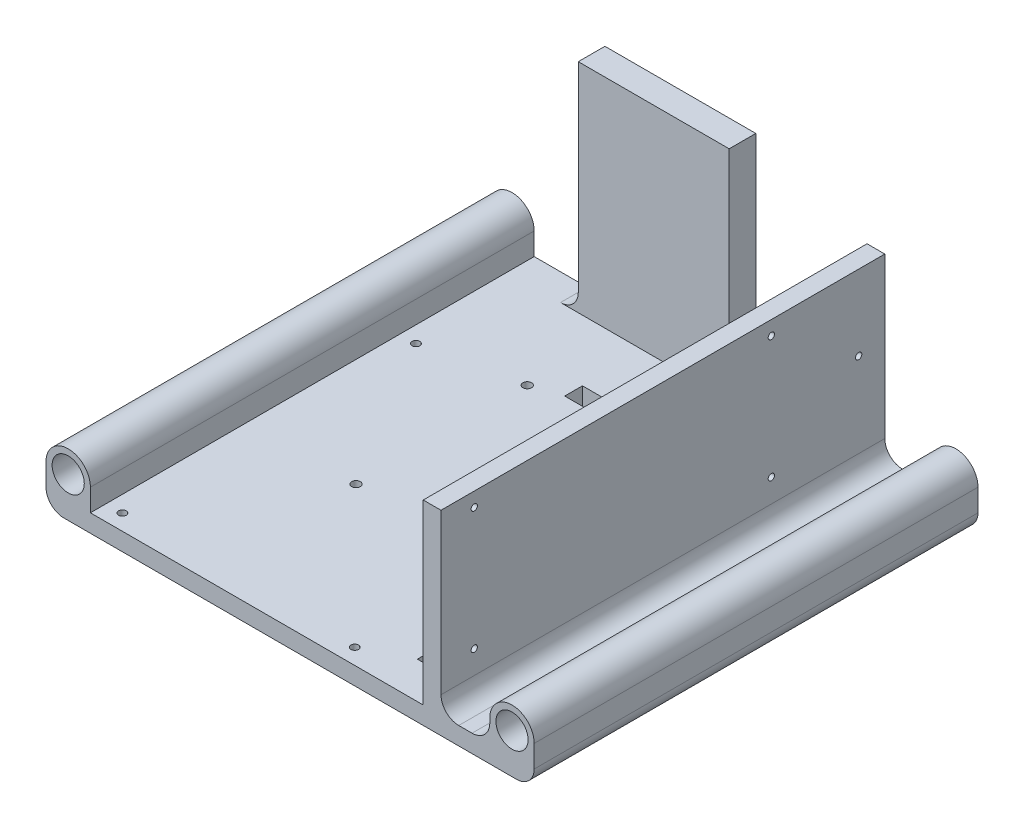
SolidWorks part; units mm, degrees
ref_plane "Front Plane" through (0, 0, 0) normal (0, 0, 1) x (1, 0, 0)
ref_plane "Top Plane" through (0, 0, 0) normal (0, 1, 0) x (1, 0, 0)
ref_plane "Right Plane" through (0, 0, 0) normal (1, 0, 0) x (0, 0, -1)
sketch "Sketch1" plane through (0, 0, 0) normal (0, 0, 1) x (1, 0, 0)
  line L21 (-0.4677, 0.9705) -> (-0.4677, -10.4595)
  line L22 (-0.4677, -10.4595) -> (139.2323, -10.4595)
  line L23 (139.2323, -10.4595) -> (139.2323, 0.9705)
  line L24 (12.2323, 0.9705) -> (12.2323, -5.3795)
  line L25 (12.2323, -5.3795) -> (126.5323, -5.3795)
  line L26 (126.5323, -5.3795) -> (126.5323, 0.9705)
  circle A8 centre (5.8823, 0.9705) radius 4.6037
  circle A9 centre (132.8823, 0.9705) radius 4.6037
  arc A13 (12.2323, 0.9705) -> (-0.4677, 0.9705) centre (5.8823, 0.9705) ccw
  arc A14 (139.2323, 0.9705) -> (126.5323, 0.9705) centre (132.8823, 0.9705) ccw
  point P23 (0, 0)
  dimension "D1" = 139.7
  dimension "D2" = 5.08
  dimension "D6" = 9.2075
  dimension "D5" = 127
extrude "Boss-Extrude1" add sketch "Sketch1" along normal blind 127
sketch "Sketch3" plane through (0, -10.4595, 0) normal (0, -1, 0) x (1, 0, 0)
  line L0 (75.7323, 119.583) -> (75.7323, 6.3354) construction
  line L2 (139.2323, 127) -> (139.2323, 0) construction
  line L20 (75.7323, 63.04) -> (81.2978, 63.04) construction
  circle A0 centre (101.1323, 81.883) radius 1.25
  circle A1 centre (43.1323, 81.883) radius 1.25
  circle A2 centre (43.1323, 32.883) radius 1.25
  circle A3 centre (101.1323, 32.883) radius 1.25
  circle A4 centre (93.2323, 9.583) radius 0.9 construction
  circle A5 centre (93.2323, 94.583) radius 0.9 construction
  circle A6 centre (75.7323, 119.583) radius 0.9 construction
  circle A7 centre (58.2323, 94.583) radius 0.9 construction
  circle A8 centre (58.2323, 9.583) radius 0.9 construction
  point P25 (130.2569, 58.4424)
  point P30 (13.2512, 58.4424)
  dimension "D5" = 2.5
  dimension "D6" = 1.8
  dimension "D1" = 58
  dimension "D2" = 49
  dimension "D3" = 38.1
  dimension "D4" = 25.4
  dimension "D7" = 35
  dimension "D8" = 17.5
  dimension "D9" = 25
  dimension "D10" = 85
  dimension "D11" = 12.7
extrude "Cut-Extrude3" cut sketch "Sketch3" against normal through all
sketch "Sketch4" plane through (0, -5.3795, 0) normal (0, 1, 0) x (1, 0, 0)
  line L0 (16.878, -38.479) -> (83.378, -38.479) construction
  line L1 (50.128, -38.479) -> (50.128, -76.4797) construction
  circle A0 centre (16.878, -38.479) radius 1.1
  circle A1 centre (16.878, -122.479) radius 1.1
  circle A2 centre (83.378, -38.479) radius 1.1
  circle A3 centre (83.378, -122.479) radius 1.1
  dimension "D1" = 2.2
  dimension "D2" = 66.5
  dimension "D3" = 84
extrude "Cut-Extrude4" cut sketch "Sketch4" against normal through all
sketch "Sketch5" plane through (0, -5.3795, 0) normal (0, 1, 0) x (1, 0, 0)
  line L0 (126.5323, 0) -> (12.2323, 0) construction
  line L1 (107.4823, 0) -> (112.5623, 0)
  line L2 (107.4823, 0) -> (107.4823, -127)
  line L3 (107.4823, -127) -> (112.5623, -127)
  line L4 (112.5623, 0) -> (112.5623, -127)
  line L5 (126.5323, -127) -> (12.2323, -127) construction
  line L6 (126.5323, -127) -> (126.5323, 0) construction
  dimension "D1" = 5.08
  dimension "D2" = 13.97
extrude "Boss-Extrude2" add sketch "Sketch5" along normal blind 50.8
sketch "Sketch6" plane through (107.4823, 0, 0) normal (-1, 0, 0) x (0, 0, 1)
  line L0 (32.475, 6.3565) -> (32.475, 41.3565) construction
  line L1 (0, 45.4205) -> (127, 45.4205) construction
  line L2 (127, 45.4205) -> (127, -5.3795) construction
  circle A0 centre (32.475, 6.3565) radius 0.9
  circle A1 centre (32.475, 41.3565) radius 0.9
  circle A2 centre (117.475, 6.3565) radius 0.9
  circle A3 centre (117.475, 41.3565) radius 0.9
  circle A4 centre (7.475, 23.8565) radius 0.9
  point P10 (32.475, 23.8565)
  dimension "D4" = 1.8
  dimension "D1" = 17.5
  dimension "D2" = 85
  dimension "D3" = 25
  dimension "D5" = 4.064
  dimension "D6" = 9.525
extrude "Cut-Extrude5" cut sketch "Sketch6" against normal up to surface (5.08 mm away) up to face at (112.5623, 20.0205, 63.5)
sketch "Sketch7" plane through (0, -5.3795, 0) normal (0, 1, 0) x (1, 0, 0)
  line L0 (107.4823, 0) -> (107.4823, -127) construction
  line L1 (101.0497, -5.08) -> (107.4823, -5.08)
  line L2 (101.0497, -5.08) -> (101.0497, -29.3604)
  line L3 (101.0497, -29.3604) -> (107.4823, -29.3604)
  line L4 (107.4823, -5.08) -> (107.4823, -29.3604)
  line L5 (107.4823, 0) -> (12.2323, 0) construction
  line L7 (51.1634, -25.1224) -> (76.5634, -25.1224)
  line L8 (51.1634, -25.1224) -> (51.1634, -30.2024)
  line L9 (51.1634, -30.2024) -> (76.5634, -30.2024)
  line L10 (76.5634, -25.1224) -> (76.5634, -30.2024)
  line L11 (95.2813, -97.2864) -> (102.8155, -97.2864)
  line L12 (95.2813, -97.2864) -> (95.2813, -116.4752)
  line L13 (95.2813, -116.4752) -> (102.8155, -116.4752)
  line L14 (102.8155, -97.2864) -> (102.8155, -116.4752)
  dimension "D1" = 5.08
  dimension "D2" = 5.08
  dimension "D3" = 25.4
extrude "Cut-Extrude6" cut sketch "Sketch7" against normal through all
fillet "Fillet1" radius 5.08 4 edges at (112.5623, -5.3795, 63.5) (126.5323, -5.3795, 63.5) (-0.4677, -10.4595, 63.5) (139.2323, -10.4595, 63.5)
sketch "Sketch8" plane through (0, -5.3795, 0) normal (0, 1, 0) x (1, 0, 0)
  line L0 (107.4823, 0) -> (12.2323, 0) construction
  line L1 (32.4697, 0) -> (75.6497, 0)
  line L2 (32.4697, 0) -> (32.4697, -7.62)
  line L3 (32.4697, -7.62) -> (75.6497, -7.62)
  line L4 (75.6497, 0) -> (75.6497, -7.62)
  line L5 (101.0497, -5.08) -> (101.0497, -29.3604) construction
  dimension "D1" = 43.18
  dimension "D2" = 7.62
  dimension "D3" = 25.4
extrude "Boss-Extrude3" add sketch "Sketch8" along normal blind 62.23
fillet "Fillet2" radius 5.08 2 edges at (32.4697, -5.3795, 3.81) (75.6497, -5.3795, 3.81)
